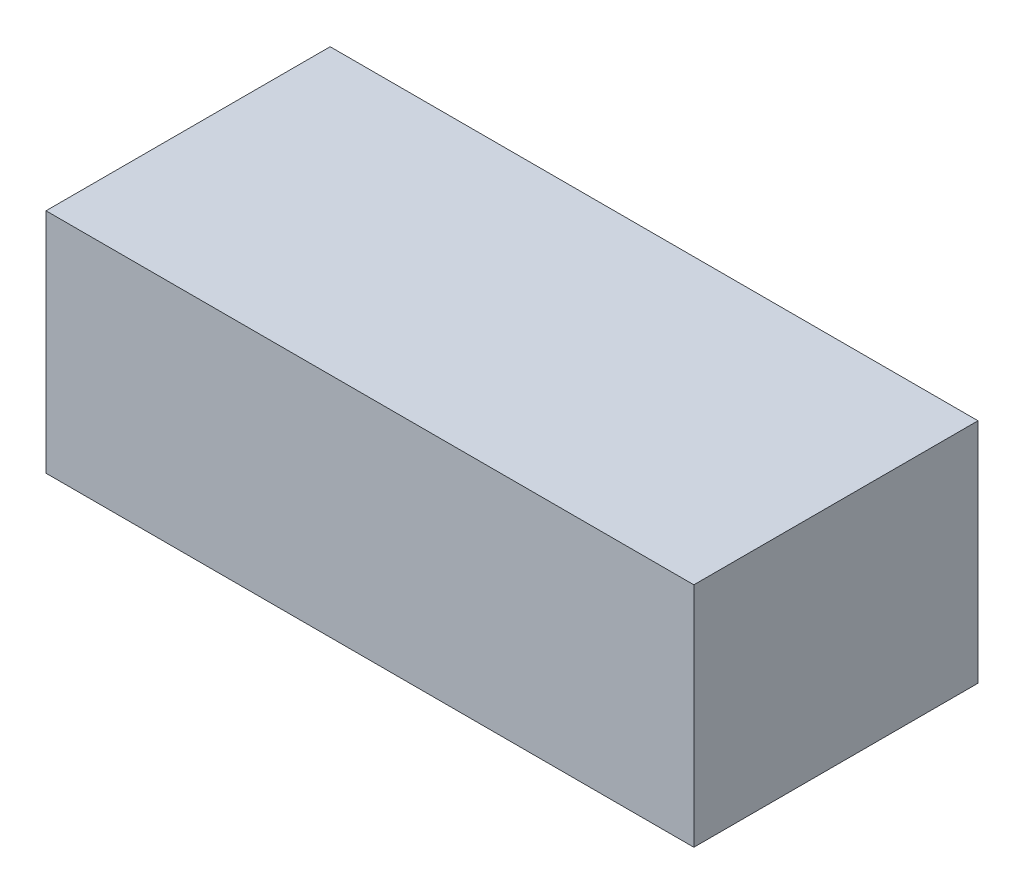
SolidWorks part; units mm, degrees
ref_plane "Front Plane" through (0, 0, 0) normal (0, 0, 1) x (1, 0, 0)
ref_plane "Top Plane" through (0, 0, 0) normal (0, 1, 0) x (1, 0, 0)
ref_plane "Right Plane" through (0, 0, 0) normal (1, 0, 0) x (0, 0, -1)
sketch "Sketch2" plane through (0, 0, 0) normal (0, 1, 0) x (1, 0, 0)
  line L1 (-28.5, 12.5) -> (28.5, 12.5)
  line L2 (-28.5, 12.5) -> (-28.5, -12.5)
  line L3 (-28.5, -12.5) -> (28.5, -12.5)
  line L4 (28.5, 12.5) -> (28.5, -12.5)
  line L5 (-28.5, 12.5) -> (28.5, -12.5) construction
  line L6 (-28.5, -12.5) -> (28.5, 12.5) construction
  point P0 (0, 0)
  dimension "D1" = 57
  dimension "D2" = 25
extrude "Boss-Extrude1" add sketch "Sketch2" along normal blind 20
